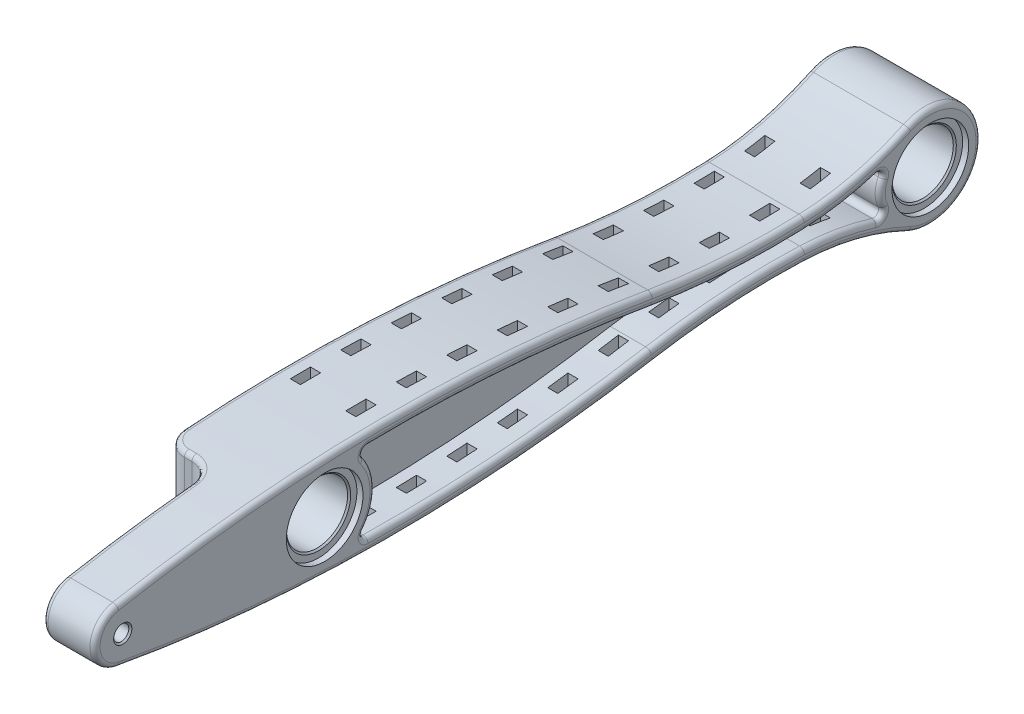
SolidWorks part; units mm, degrees
ref_plane "前视基准面" through (0, 0, 0) normal (0, 0, 1) x (1, 0, 0)
ref_plane "上视基准面" through (0, 0, 0) normal (0, 1, 0) x (1, 0, 0)
ref_plane "右视基准面" through (0, 0, 0) normal (1, 0, 0) x (0, 0, -1)
sketch "草图1" plane through (0, 0, 0) normal (1, 0, 0) x (0, 0, -1)
  line L0 (0, 0) -> (31.4676, 0) construction
  line L1 (65, 6) -> (65, 0)
  line L2 (95, 0) -> (95, 4)
  circle A0 centre (0, 0) radius 6.05
  circle A1 centre (120, 0) radius 6.05
  circle A2 centre (-40, 0) radius 1.5
  circle A4 centre (0, 0) radius 10.05
  circle A5 centre (120, 0) radius 10.05
  circle A6 centre (-40, 0) radius 5.5
  arc A7 (-40.9896, 5.4102) -> (65, 6) centre (13.6695, -293.4026) cw
  arc A8 (65, 6) -> (95, 4) centre (89.6532, 149.7985) ccw
  arc A9 (95, 4) -> (115.6782, 9.0733) centre (93.0736, 56.5295) ccw
  arc A10 (-40.9896, -5.4102) -> (65, -6) centre (13.6695, 293.4026) ccw
  arc A11 (65, -6) -> (95, -4) centre (89.6532, -149.7985) cw
  arc A12 (95, -4) -> (115.6782, -9.0733) centre (93.0736, -56.5295) cw
  dimension "D2" = 12.1
  dimension "D3" = 12.1
  dimension "D4" = 3
  dimension "D6" = 4
  dimension "D7" = 4
  dimension "D10" = 4
  dimension "D1" = 120
  dimension "D5" = 40
  dimension "D8" = 6
  dimension "D9" = 65
  dimension "D12" = 4
  dimension "40" = 30
extrude "凸台-拉伸1" add sketch "草图1" along normal blind 19.8 contours A4 L0 L1 A7 | L0 A4 A10 A11 A12 A5 | A4 L0 A0 | L0 A4 A0 | L0 A6 A10 A4 | A6 L0 A4 A7 | A6 L0 A2 | L0 A6 A2 | L1 L0 L2 A8 | L2 L0 A5 A9 | A5 L0 A1 | L0 A5 A1
sketch "草图3" plane through (0, 0, 0) normal (0, 1, 0) x (1, 0, 0)
  line L0 (0, 0) -> (20, 0) construction
  line L5 (9.5, 0) -> (9.5, -52)
  line L6 (9.5, -52) -> (0, -52)
  line L7 (0, -52) -> (0, -12)
  line L8 (0, -12) -> (9.5, -12)
  line L9 (0, 65) -> (0, -40.9896) construction
  line L10 (3, 14) -> (5, 14)
  line L11 (3, 14) -> (3, 10)
  line L12 (3, 10) -> (5, 10)
  line L13 (5, 14) -> (5, 10)
  line L14 (5, 24) -> (5, 20)
  line L15 (3, 20) -> (5, 20)
  line L16 (3, 24) -> (3, 20)
  line L17 (3, 24) -> (5, 24)
  line L18 (5, 34) -> (5, 30)
  line L19 (3, 30) -> (5, 30)
  line L20 (3, 34) -> (3, 30)
  line L21 (3, 34) -> (5, 34)
  line L22 (5, 44) -> (5, 40)
  line L23 (3, 40) -> (5, 40)
  line L24 (3, 44) -> (3, 40)
  line L25 (3, 44) -> (5, 44)
  line L26 (5, 54) -> (5, 50)
  line L27 (3, 50) -> (5, 50)
  line L28 (3, 54) -> (3, 50)
  line L29 (3, 54) -> (5, 54)
  line L30 (5, 64) -> (5, 60)
  line L31 (3, 60) -> (5, 60)
  line L32 (3, 64) -> (3, 60)
  line L33 (3, 64) -> (5, 64)
  line L34 (5, 74) -> (5, 70)
  line L35 (3, 70) -> (5, 70)
  line L36 (3, 74) -> (3, 70)
  line L37 (3, 74) -> (5, 74)
  line L38 (5, 84) -> (5, 80)
  line L39 (3, 80) -> (5, 80)
  line L40 (3, 84) -> (3, 80)
  line L41 (3, 84) -> (5, 84)
  line L42 (5, 94) -> (5, 90)
  line L43 (3, 90) -> (5, 90)
  line L44 (3, 94) -> (3, 90)
  line L45 (3, 94) -> (5, 94)
  line L46 (5, 104) -> (5, 100)
  line L47 (3, 100) -> (5, 100)
  line L48 (3, 104) -> (3, 100)
  line L49 (3, 104) -> (5, 104)
  line L51 (16, 80) -> (14, 80)
  line L52 (14, 84) -> (14, 80)
  line L53 (16, 84) -> (16, 80)
  line L54 (16, 84) -> (14, 84)
  line L55 (16, 90) -> (14, 90)
  line L56 (16, 94) -> (16, 90)
  line L57 (14, 94) -> (14, 90)
  line L58 (16, 94) -> (14, 94)
  line L59 (16, 100) -> (14, 100)
  line L60 (16, 104) -> (16, 100)
  line L61 (14, 104) -> (14, 100)
  line L62 (16, 104) -> (14, 104)
  line L63 (16, 74) -> (16, 70)
  line L64 (16, 74) -> (14, 74)
  line L65 (14, 74) -> (14, 70)
  line L66 (16, 70) -> (14, 70)
  line L67 (16, 64) -> (14, 64)
  line L68 (16, 64) -> (16, 60)
  line L69 (16, 60) -> (14, 60)
  line L70 (14, 64) -> (14, 60)
  line L71 (16, 50) -> (14, 50)
  line L72 (16, 54) -> (16, 50)
  line L73 (16, 54) -> (14, 54)
  line L74 (14, 54) -> (14, 50)
  line L75 (16, 40) -> (14, 40)
  line L76 (16, 44) -> (16, 40)
  line L77 (16, 44) -> (14, 44)
  line L78 (14, 44) -> (14, 40)
  line L79 (16, 34) -> (14, 34)
  line L80 (14, 34) -> (14, 30)
  line L81 (16, 34) -> (16, 30)
  line L82 (16, 30) -> (14, 30)
  line L83 (16, 24) -> (16, 20)
  line L84 (16, 24) -> (14, 24)
  line L85 (14, 24) -> (14, 20)
  line L86 (16, 20) -> (14, 20)
  line L87 (16, 14) -> (14, 14)
  line L88 (16, 14) -> (16, 10)
  line L89 (14, 14) -> (14, 10)
  line L90 (16, 10) -> (14, 10)
  dimension "D1" = 20
  dimension "D2" = 12
  dimension "D3" = 40
  dimension "D4" = 3
  dimension "D5" = 10
  dimension "D6" = 4
  dimension "D7" = 2
  dimension "D9" = 10
  dimension "D10" = 9.5
  dimension "D8" = 10
extrude "切除-拉伸2" cut sketch "草图3" against normal through all both and the other way through all contours L8 L7 L6 L5 | L11 L10 L13 L12 | L87 L89 L90 L88 | L83 L86 L85 L84 | L14 L15 L16 L17 | L18 L19 L20 L21 | L79 L80 L82 L81 | L75 L78 L77 L76 | L22 L23 L24 L25 | L26 L27 L28 L29 | L71 L74 L73 L72 | L67 L70 L69 L68 | L30 L31 L32 L33 | L34 L35 L36 L37 | L63 L66 L65 L64 | L51 L52 L54 L53 | L38 L39 L40 L41 | L42 L43 L44 L45 | L55 L57 L58 L56 | L59 L61 L62 L60 | L46 L47 L48 L49
sketch "草图4" plane through (19.8, 0, 0) normal (1, 0, 0) x (0, 0, -1)
  circle A0 centre (0, 0) radius 6.05 construction
  circle A1 centre (-40, 0) radius 1.5 construction
  circle A2 centre (120, 0) radius 6.05 construction
  circle A3 centre (-40, 0) radius 1.5
  circle A4 centre (0, 0) radius 6.05
  circle A5 centre (120, 0) radius 6.05
  arc A7 (64.5776, 3.536) -> (6.2854, 7.7778) centre (13.6695, -293.4026) ccw
  arc A8 (115.6782, -9.0733) -> (115.6782, 9.0733) centre (120, 0) ccw
  arc A9 (95, 4) -> (115.6782, 9.0733) centre (93.0736, 56.5295) ccw
  arc A10 (65, 6) -> (95, 4) centre (89.6532, 149.7985) ccw
  arc A11 (65, 6) -> (-40.9896, 5.4102) centre (13.6695, -293.4026) ccw
  arc A12 (-40.9896, 5.4102) -> (-40.9896, -5.4102) centre (-40, 0) ccw
  arc A13 (-40.9896, -5.4102) -> (65, -6) centre (13.6695, 293.4026) ccw
  arc A14 (95, -4) -> (65, -6) centre (89.6532, -149.7985) ccw
  arc A15 (115.6782, -9.0733) -> (95, -4) centre (93.0736, -56.5295) ccw
  arc A16 (115.6782, -9.0733) -> (115.6782, 9.0733) centre (120, 0) ccw
  arc A17 (95, 4) -> (115.6782, 9.0733) centre (93.0736, 56.5295) ccw
  arc A18 (65, 6) -> (95, 4) centre (89.6532, 149.7985) ccw
  arc A19 (65, 6) -> (-40.9896, 5.4102) centre (13.6695, -293.4026) ccw
  arc A20 (-40.9896, 5.4102) -> (-40.9896, -5.4102) centre (-40, 0) ccw
  arc A21 (-40.9896, -5.4102) -> (65, -6) centre (13.6695, 293.4026) ccw
  arc A22 (95, -4) -> (65, -6) centre (89.6532, -149.7985) ccw
  arc A23 (115.6782, -9.0733) -> (95, -4) centre (93.0736, -56.5295) ccw
  arc A26 (95.0916, -1.5017) -> (64.5776, -3.536) centre (89.6532, -149.7985) ccw
  arc A27 (113.7687, -5.5016) -> (95.0916, -1.5017) centre (93.0736, -56.5295) ccw
  arc A29 (95.0916, 1.5017) -> (113.7687, 5.5016) centre (93.0736, 56.5295) ccw
  arc A30 (64.5776, 3.536) -> (95.0916, 1.5017) centre (89.6532, 149.7985) ccw
  arc A31 (6.2854, -7.7778) -> (6.2854, 7.7778) centre (0, 0) ccw
  arc A32 (64.5776, 3.536) -> (-40.5398, 2.951) centre (13.6695, -293.4026) ccw construction
  arc A33 (6.2854, -7.7778) -> (64.5776, -3.536) centre (13.6695, 293.4026) ccw
  arc A34 (-40.5398, -2.951) -> (64.5776, -3.536) centre (13.6695, 293.4026) ccw construction
  arc A35 (-40.5398, 2.951) -> (-40.5398, -2.951) centre (-40, 0) ccw construction
  arc A36 (113.7687, 5.5016) -> (113.7687, -5.5016) centre (116, 0) ccw
  arc A37 (95.0916, 1.5017) -> (116.7533, 6.8162) centre (93.0736, 56.5295) ccw construction
  arc A38 (116.7533, -6.8162) -> (116.7533, 6.8162) centre (120, 0) ccw construction
  arc A39 (116.7533, -6.8162) -> (95.0916, -1.5017) centre (93.0736, -56.5295) ccw construction
  dimension "D2" = 4
  dimension "D3" = 2.5
  dimension "D4" = 10
  dimension "D1" = 0
extrude "切除-拉伸3" cut sketch "草图4" against normal blind 8 contours A27 A26 A33 A31 A7 A30 A29 A36
sketch "草图5" plane through (0, 0, 0) normal (-1, 0, 0) x (0, 0, 1)
  line L1 (12, -9.2817) -> (12, 9.2817)
  line L5 (12, -9.2817) -> (12, 9.2817)
  arc A7 (12, 9.2817) -> (-65, 6) centre (-13.6695, -293.4026) ccw
  arc A11 (12, 9.2817) -> (-65, 6) centre (-13.6695, -293.4026) ccw
  arc A22 (-95, 4) -> (-65, 6) centre (-89.6532, 149.7985) ccw
  arc A26 (-6.2854, 7.7778) -> (-6.2854, -7.7778) centre (0, 0) ccw
  arc A27 (-95, 4) -> (-65, 6) centre (-89.6532, 149.7985) ccw
  arc A28 (-64.5776, -3.536) -> (-6.2854, -7.7778) centre (-13.6695, 293.4026) ccw
  arc A29 (-64.5776, -3.536) -> (-95.0916, -1.5017) centre (-89.6532, -149.7985) ccw
  arc A30 (-95.0916, -1.5017) -> (-113.7687, -5.5016) centre (-93.0736, -56.5295) ccw
  arc A32 (-113.7687, -5.5016) -> (-113.7687, 5.5016) centre (-116, 0) ccw
  arc A33 (-115.6782, 9.0733) -> (-95, 4) centre (-93.0736, 56.5295) ccw
  arc A34 (-113.7687, 5.5016) -> (-95.0916, 1.5017) centre (-93.0736, 56.5295) ccw
  arc A35 (-95.0916, 1.5017) -> (-64.5776, 3.536) centre (-89.6532, 149.7985) ccw
  arc A36 (-6.2854, 7.7778) -> (-64.5776, 3.536) centre (-13.6695, -293.4026) ccw
  arc A38 (-6.2854, 7.7778) -> (-6.2854, -7.7778) centre (0, 0) ccw
  arc A40 (-64.5776, -3.536) -> (-6.2854, -7.7778) centre (-13.6695, 293.4026) ccw
  arc A41 (-64.5776, -3.536) -> (-95.0916, -1.5017) centre (-89.6532, -149.7985) ccw
  arc A42 (-95.0916, -1.5017) -> (-113.7687, -5.5016) centre (-93.0736, -56.5295) ccw
  arc A44 (-113.7687, -5.5016) -> (-113.7687, 5.5016) centre (-116, 0) ccw
  arc A46 (-113.7687, 5.5016) -> (-95.0916, 1.5017) centre (-93.0736, 56.5295) ccw
  arc A47 (-95.0916, 1.5017) -> (-64.5776, 3.536) centre (-89.6532, 149.7985) ccw
  arc A48 (-6.2854, 7.7778) -> (-64.5776, 3.536) centre (-13.6695, -293.4026) ccw
  arc A50 (-115.6782, 9.0733) -> (-95, 4) centre (-93.0736, 56.5295) ccw
  arc A53 (-115.6782, 9.0733) -> (-115.6782, -9.0733) centre (-120, 0) ccw
  arc A55 (-115.6782, 9.0733) -> (-115.6782, -9.0733) centre (-120, 0) ccw
  arc A56 (-95, -4) -> (-115.6782, -9.0733) centre (-93.0736, -56.5295) ccw
  arc A57 (-95, -4) -> (-115.6782, -9.0733) centre (-93.0736, -56.5295) ccw
  arc A58 (-65, -6) -> (-95, -4) centre (-89.6532, -149.7985) ccw
  arc A59 (-65, -6) -> (-95, -4) centre (-89.6532, -149.7985) ccw
  arc A68 (-65, -6) -> (12, -9.2817) centre (-13.6695, 293.4026) ccw
  arc A69 (-65, -6) -> (12, -9.2817) centre (-13.6695, 293.4026) ccw
  dimension "D1" = 0
  dimension "D2" = 0
extrude "切除-拉伸4" cut sketch "草图5" against normal blind 8 contours A38 A40 A41 A42 A44 A46 A47 A48
sketch "草图8" plane through (0, 0, 0) normal (-1, 0, 0) x (0, 0, 1)
  line L1 (12, -9.2817) -> (12, 9.2817)
  line L2 (12, -9.2817) -> (12, 9.2817)
  circle A0 centre (0, 0) radius 6.05 construction
  circle A1 centre (0, 0) radius 6.05
  circle A2 centre (0, 0) radius 7.6
  circle A3 centre (-120, 0) radius 7.6
  arc A7 (12, 9.2817) -> (-65, 6) centre (-13.6695, -293.4026) ccw
  arc A8 (-95, 4) -> (-65, 6) centre (-89.6532, 149.7985) ccw
  arc A9 (-115.6782, 9.0733) -> (-95, 4) centre (-93.0736, 56.5295) ccw
  arc A10 (-115.6782, 9.0733) -> (-115.6782, -9.0733) centre (-120, 0) ccw
  arc A11 (-95, -4) -> (-115.6782, -9.0733) centre (-93.0736, -56.5295) ccw
  arc A12 (-65, -6) -> (-95, -4) centre (-89.6532, -149.7985) ccw
  arc A13 (-65, -6) -> (12, -9.2817) centre (-13.6695, 293.4026) ccw
  arc A14 (12, 9.2817) -> (-65, 6) centre (-13.6695, -293.4026) ccw
  arc A15 (-95, 4) -> (-65, 6) centre (-89.6532, 149.7985) ccw
  arc A16 (-115.6782, 9.0733) -> (-95, 4) centre (-93.0736, 56.5295) ccw
  arc A17 (-115.6782, 9.0733) -> (-115.6782, -9.0733) centre (-120, 0) ccw
  arc A18 (-95, -4) -> (-115.6782, -9.0733) centre (-93.0736, -56.5295) ccw
  arc A19 (-65, -6) -> (-95, -4) centre (-89.6532, -149.7985) ccw
  arc A20 (-65, -6) -> (12, -9.2817) centre (-13.6695, 293.4026) ccw
  circle M17 centre (0, 0) radius 6.05
  dimension "D2" = 15.2
  dimension "D3" = 15.2
  dimension "D1" = 0
extrude "切除-拉伸7" cut sketch "草图8" against normal blind 1.2 contours A2 M17 | M17 | A3
sketch "草图9" plane through (19.8, 0, 0) normal (1, 0, 0) x (0, 0, -1)
  circle A0 centre (0, 0) radius 6.05 construction
  circle A1 centre (0, 0) radius 6.05
  circle A2 centre (0, 0) radius 7.6
  circle A3 centre (120, 0) radius 7.6
  arc A8 (115.6782, -9.0733) -> (115.6782, 9.0733) centre (120, 0) ccw
  arc A9 (95, 4) -> (115.6782, 9.0733) centre (93.0736, 56.5295) ccw
  arc A10 (65, 6) -> (95, 4) centre (89.6532, 149.7985) ccw
  arc A11 (65, 6) -> (-40.9896, 5.4102) centre (13.6695, -293.4026) ccw
  arc A12 (-40.9896, 5.4102) -> (-40.9896, -5.4102) centre (-40, 0) ccw
  arc A13 (-40.9896, -5.4102) -> (65, -6) centre (13.6695, 293.4026) ccw
  arc A14 (95, -4) -> (65, -6) centre (89.6532, -149.7985) ccw
  arc A15 (115.6782, -9.0733) -> (95, -4) centre (93.0736, -56.5295) ccw
  arc A16 (115.6782, -9.0733) -> (115.6782, 9.0733) centre (120, 0) ccw
  arc A17 (95, 4) -> (115.6782, 9.0733) centre (93.0736, 56.5295) ccw
  arc A18 (65, 6) -> (95, 4) centre (89.6532, 149.7985) ccw
  arc A19 (65, 6) -> (-40.9896, 5.4102) centre (13.6695, -293.4026) ccw
  arc A20 (-40.9896, 5.4102) -> (-40.9896, -5.4102) centre (-40, 0) ccw
  arc A21 (-40.9896, -5.4102) -> (65, -6) centre (13.6695, 293.4026) ccw
  arc A22 (95, -4) -> (65, -6) centre (89.6532, -149.7985) ccw
  arc A23 (115.6782, -9.0733) -> (95, -4) centre (93.0736, -56.5295) ccw
  circle M19 centre (0, 0) radius 6.05
  dimension "D2" = 15.2
  dimension "D3" = 15.2
  dimension "D1" = 0
extrude "切除-拉伸8" cut sketch "草图9" against normal blind 1.2 contours A2 M19 | M19 | A3
fillet "圆角4" radius 1 8 edges at (15.8, -5.5016, -113.7687) (15.8, 5.5016, -113.7687) (15.8, -7.7778, -6.2854) (15.8, 7.7778, -6.2854) (4, -7.7778, -6.2854) (4, 7.7778, -6.2854) (4, -5.5016, -113.7687) (4, 5.5016, -113.7687)
fillet "圆角6" radius 4 2 edges at (9.5, 0, 12) (0, 0, 12)
chamfer "倒角1" distance 0.3 angle 45 6 edges at (9.5, 0, 41.5) (19.8, 0, 38.5) (18.6, 0, -6.05) (1.2, 0, 6.05) (1.2, 0, -113.95) (18.6, 0, -126.05)
fillet "圆角9" radius 1 48 edges at (1.5077, -9.3544, 11.1286) (8.6171, -9.1514, 13.4933) (9.5, -7.4226, 28.5312) (9.5, 0, 45.5) (9.5, 7.4226, 28.5312) (7.9918, 9.2066, 12.8709) (0.8809, 9.4049, 10.5042) (19.8, 1.7307, -79.782) (19.8, 6.9872, -36.6935) (19.8, 7.2539, -7.7222) (19.8, 0, -10) (19.8, -7.2539, -7.7222) (19.8, -6.9872, -36.6935) (19.8, -1.7307, -79.782) (19.8, -2.2519, -102.3516) (19.8, -3.6549, -110.5025) (19.8, 0, -110.0631) (19.8, 3.6549, -110.5025) (19.8, 2.2519, -102.3516) (0, -5.4787, -105.5986) (19.8, -5.4787, -105.5986) (0, -4.2251, -79.9483) (19.8, -4.2251, -79.9483) (19.8, -10.3636, -11.9793) (19.8, 0, 45.5) (19.8, 10.3636, -11.9793) (0, 4.2251, -79.9483) (19.8, 4.2251, -79.9483) (0, 5.4787, -105.5986) (19.8, 5.4787, -105.5986) (0, 0, -130.05) (19.8, 0, -130.05) (0, 10.0007, -28.6085) (0, -10.0007, -28.6085) (0, 2.2519, -102.3516) (0, 3.6549, -110.5025) (0, 0, -110.0631) (0, -3.6549, -110.5025) (0, -2.2519, -102.3516) (0, -1.7307, -79.782) (0, -6.9872, -36.6935) (0, -7.2539, -7.7222) (0, 0, -10) (0, 7.2539, -7.7222) (0, 6.9872, -36.6935) (0, 1.7307, -79.782) (4.75, -9.2817, 12) (4.75, 9.2817, 12)
